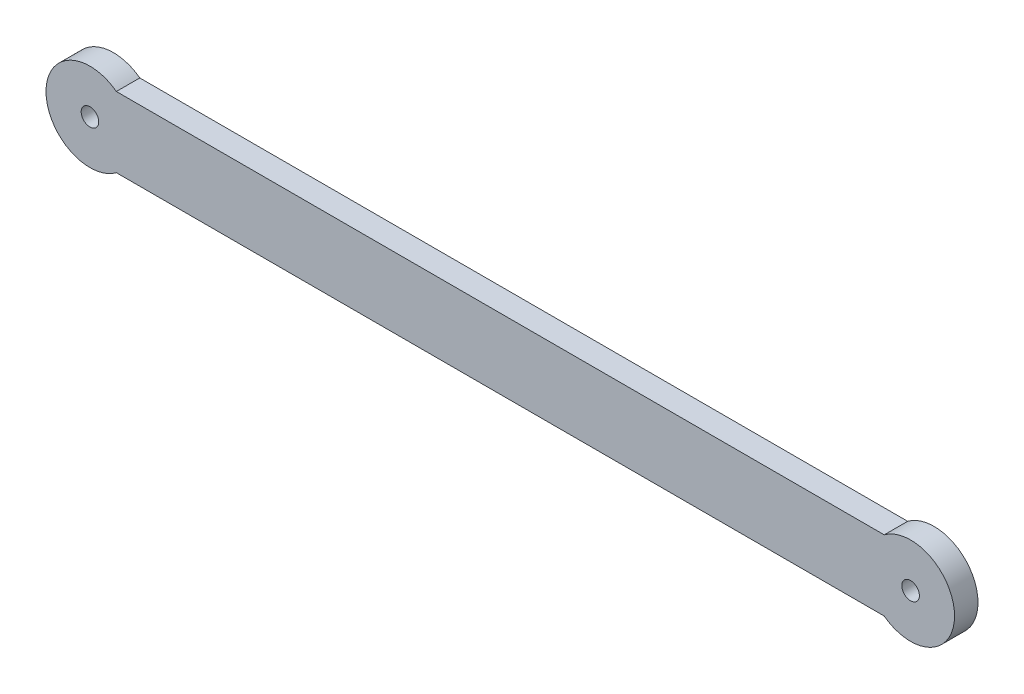
SolidWorks part; units mm, degrees
material "Acrílico (Impacto medio-alto)"
ref_plane "Piano frontale" through (0, 0, 0) normal (0, 0, 1) x (1, 0, 0)
ref_plane "Piano superiore" through (0, 0, 0) normal (0, 1, 0) x (1, 0, 0)
ref_plane "Piano destro" through (0, 0, 0) normal (1, 0, 0) x (0, 0, -1)
sketch "Schizzo1" plane through (0, 0, 0) normal (0, 0, 1) x (1, 0, 0)
  line L0 (0, 0) -> (1.5, 0) construction
  line L1 (4.5, -6) -> (135.5, -6)
  line L2 (4.5, 6) -> (135.5, 6)
  line L3 (0, 6) -> (140, 6) construction
  line L4 (0, -6) -> (140, -6) construction
  line L5 (138.5, 0) -> (140, 0) construction
  line L6 (0, 0) -> (140, 0) construction
  circle A0 centre (0, 0) radius 1.5
  circle A1 centre (140, 0) radius 1.5
  arc A2 (4.5, 6) -> (4.5, -6) centre (0, 0) ccw
  arc A3 (135.5, -6) -> (135.5, 6) centre (140, 0) ccw
  dimension "D1" = 3
  dimension "D2" = 3
  dimension "D4" = 15
  dimension "D5" = 15
  dimension "D3" = 140
  dimension "D6" = 6
  dimension "D7" = 6
extrude "Estrusione-Estrusione1" add sketch "Schizzo1" along normal blind 4
